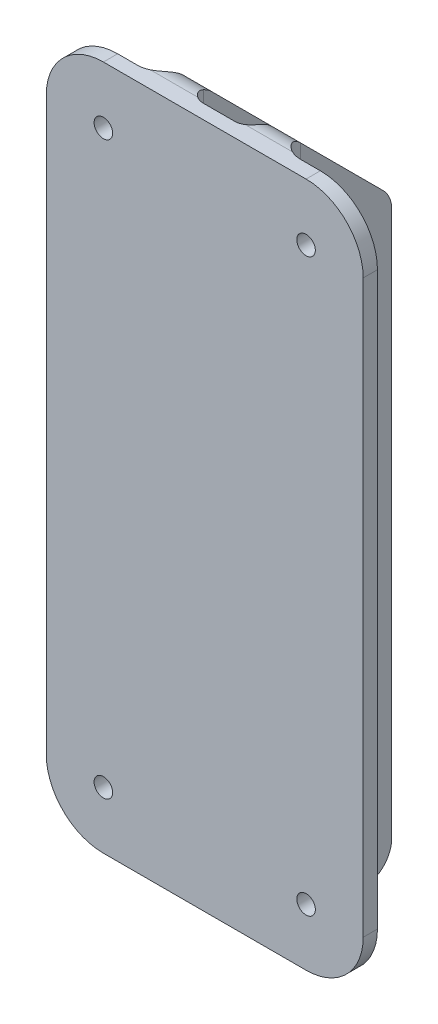
SolidWorks part; units mm, degrees
ref_plane "Front Plane" through (0, 0, 0) normal (0, 0, 1) x (1, 0, 0)
ref_plane "Top Plane" through (0, 0, 0) normal (0, 1, 0) x (1, 0, 0)
ref_plane "Right Plane" through (0, 0, 0) normal (1, 0, 0) x (0, 0, -1)
sketch "Sketch1" plane through (0, 0, 0) normal (0, 0, 1) x (1, 0, 0)
  line L1 (-55.5, 240) -> (55.5, 240)
  line L2 (-55.5, 240) -> (-55.5, 0)
  line L3 (-55.5, 0) -> (55.5, 0)
  line L4 (55.5, 240) -> (55.5, 0)
  point P4 (0, 0)
  point P5 (0, 0)
  dimension "D1" = 111
  dimension "D2" = 240
extrude "Boss-Extrude1" add sketch "Sketch1" along normal blind 5
fillet "Fillet1" radius 20 4 edges at (55.5, 0, 2.5) (-55.5, 0, 2.5) (-55.5, 240, 2.5) (55.5, 240, 2.5)
ref_plane "Plane1" through (10.5, 0, 0) normal (1, 0, 0) x (0, 0, -1)
sketch "Sketch2" plane through (10.5, 0, 0) normal (1, 0, 0) x (0, 0, -1)
  line L0 (0, 0) -> (30, 0)
  line L1 (40, 10) -> (40, 200.8579)
  line L2 (37.0711, 207.9289) -> (7.9289, 237.0711)
  line L3 (0.8579, 240) -> (0, 240)
  line L4 (0, 20) -> (0, 220) construction
  line L5 (20, 190) -> (0, 190) construction
  line L6 (-5, 240) -> (0, 240) construction
  line L7 (20, 190) -> (20, 20) construction
  line L8 (0, 0) -> (0, 240)
  arc A0 (30, 0) -> (40, 10) centre (30, 10) ccw
  arc A1 (40, 200.8579) -> (37.0711, 207.9289) centre (30, 200.8579) ccw
  arc A2 (7.9289, 237.0711) -> (0.8579, 240) centre (0.8579, 230) ccw
  circle A3 centre (20, 190) radius 4.25
  circle A4 centre (20, 20) radius 4.25
  point P13 (40, 0)
  point P18 (5, 240)
  dimension "D4" = 10
  dimension "D5" = 10
  dimension "D6" = 10
  dimension "D7" = 8.5
  dimension "D1" = 40
  dimension "D2" = 5
  dimension "D3" = 135
  dimension "D8" = 20
  dimension "D9" = 50
  dimension "D10" = 20
extrude "Boss-Extrude2" add sketch "Sketch2" along normal blind 10
fillet "Fillet2" radius 8 1 edges at (20.5, 120, 0)
fillet "Fillet3" radius 5 1 edges at (10.5, 120, 0)
mirror "Mirror1" about plane through (0, 0, 0) normal (1, 0, 0) of "Fillet3", "Fillet2", "Boss-Extrude2"
sketch "Sketch3" plane through (0, 0, 0) normal (0, 0, -1) x (-1, 0, 0)
  circle A0 centre (-35.5, 220) radius 3.25
  circle A1 centre (-35.5, 20) radius 3.25
  circle A2 centre (35.5, 20) radius 3.25
  circle A3 centre (35.5, 220) radius 3.25
  arc A4 (55.5, 220) -> (35.5, 240) centre (35.5, 220) ccw construction
  arc A5 (-35.5, 240) -> (-55.5, 220) centre (-35.5, 220) ccw construction
  arc A7 (-55.5, 20) -> (-35.5, 0) centre (-35.5, 20) ccw construction
  dimension "D1" = 6.5
extrude "Cut-Extrude1" cut sketch "Sketch3" against normal through all
sketch "Sketch4" plane through (0, 0, 0) normal (0, 0, -1) x (-1, 0, 0)
  circle A0 centre (-35.5, 220) radius 8
  circle A1 centre (35.5, 220) radius 8
  circle A2 centre (35.5, 20) radius 8
  circle A3 centre (-35.5, 20) radius 8
  dimension "D1" = 16
extrude "Cut-Extrude2" cut sketch "Sketch4" along normal through all
equation "\"D8@Sketch2\"=\"D1@Sketch2\"/2"
equation "\"D10@Sketch2\"=\"D1@Sketch2\"/2"
